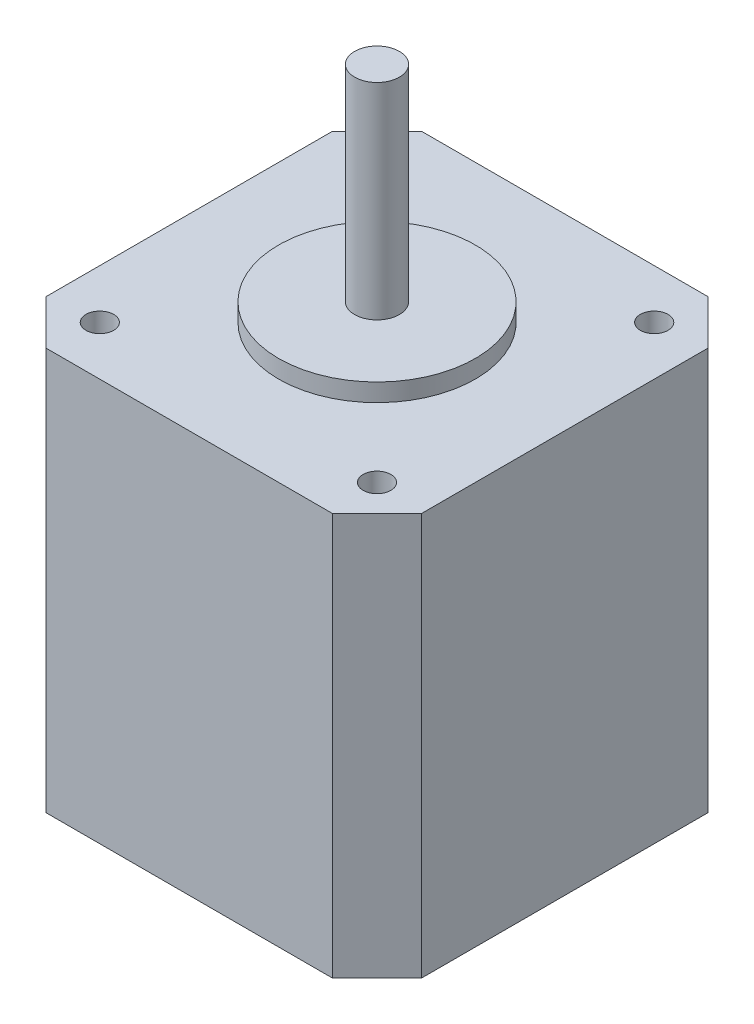
SolidWorks part; units mm, degrees
material "灰铸铁"
ref_plane "前视基准面" through (0, 0, 0) normal (0, 0, 1) x (1, 0, 0)
ref_plane "上视基准面" through (0, 0, 0) normal (0, 1, 0) x (1, 0, 0)
ref_plane "右视基准面" through (0, 0, 0) normal (1, 0, 0) x (0, 0, -1)
sketch "草图1" plane through (0, 0, 0) normal (0, 1, 0) x (1, 0, 0)
  line L0 (-16, 21) -> (-21, 16)
  line L1 (-16, 21) -> (16, 21)
  line L2 (-21, 16) -> (-21, -16)
  line L3 (-16, -21) -> (16, -21)
  line L4 (21, 16) -> (21, -16)
  line L5 (-21, 21) -> (21, -21) construction
  line L6 (-21, -21) -> (21, 21) construction
  line L7 (16, 21) -> (21, 16)
  line L8 (21, -16) -> (16, -21)
  line L9 (-21, -16) -> (-16, -21)
  point P0 (0, 0)
  dimension "D1" = 42
  dimension "D2" = 42
extrude "凸台-拉伸1" add sketch "草图1" along normal blind 45
ref_plane "基准面1" through (0, 45, 0) normal (0, 1, 0) x (1, 0, 0)
sketch "草图2" plane through (0, 45, 0) normal (0, 1, 0) x (1, 0, 0)
  circle A0 centre (0, 0) radius 11
  dimension "D1" = 22
extrude "凸台-拉伸2" add sketch "草图2" along normal blind 2
ref_plane "基准面2" through (0, 47, 0) normal (0, 1, 0) x (1, 0, 0)
sketch "草图3" plane through (0, 47, 0) normal (0, 1, 0) x (1, 0, 0)
  circle A0 centre (0, 0) radius 2.5
  dimension "D1" = 5
extrude "凸台-拉伸3" add sketch "草图3" along normal blind 23
sketch "草图4" plane through (0, 45, 0) normal (0, 1, 0) x (1, 0, 0)
  line L1 (-15.5, 15.5) -> (15.5, 15.5) construction
  line L2 (-15.5, 15.5) -> (-15.5, -15.5) construction
  line L3 (-15.5, -15.5) -> (15.5, -15.5) construction
  line L4 (15.5, 15.5) -> (15.5, -15.5) construction
  line L5 (-15.5, 15.5) -> (15.5, -15.5) construction
  line L6 (-15.5, -15.5) -> (15.5, 15.5) construction
  circle A0 centre (-15.5, 15.5) radius 1.55
  circle A1 centre (15.5, 15.5) radius 1.55
  circle A2 centre (-15.5, -15.5) radius 1.55
  circle A3 centre (15.5, -15.5) radius 1.55
  point P0 (0, 0)
  dimension "D3" = 3.1
  dimension "D4" = 3.1
  dimension "D5" = 3.1
  dimension "D6" = 3.1
  dimension "D1" = 31
  dimension "D2" = 31
extrude "切除-拉伸1" cut sketch "草图4" against normal blind 5
